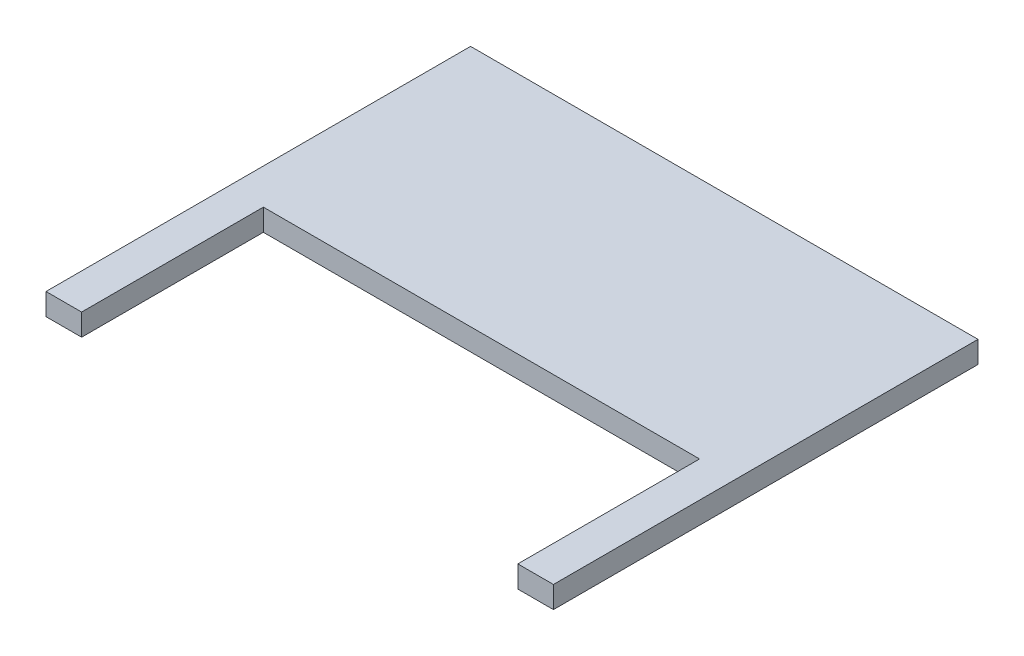
SolidWorks part; units mm, degrees
ref_plane "Front" through (0, 0, 0) normal (0, 0, 1) x (1, 0, 0)
ref_plane "Top" through (0, 0, 0) normal (0, 1, 0) x (1, 0, 0)
ref_plane "Right" through (0, 0, 0) normal (1, 0, 0) x (0, 0, -1)
sketch "Sketch1" plane through (0, 0, 0) normal (0, 1, 0) x (1, 0, 0)
  line L1 (0, 0) -> (69.8, 0)
  line L2 (0, 0) -> (0, -58.4)
  line L3 (0, -58.4) -> (69.8, -58.4)
  line L4 (69.8, 0) -> (69.8, -58.4)
  line L5 (4.9, -33.4) -> (64.9, -33.4)
  line L6 (4.9, -33.4) -> (4.9, -58.4)
  line L7 (4.9, -58.4) -> (64.9, -58.4)
  line L8 (64.9, -33.4) -> (64.9, -58.4)
  dimension "D1" = 69.8
  dimension "D2" = 58.4
  dimension "D3" = 25
  dimension "D4" = 60
  dimension "D5" = 4.9
  dimension "D6" = 0
extrude "Boss-Extrude1" add sketch "Sketch1" along normal blind 3 contours L5 L8 L3 L4 L1 L2 L6
